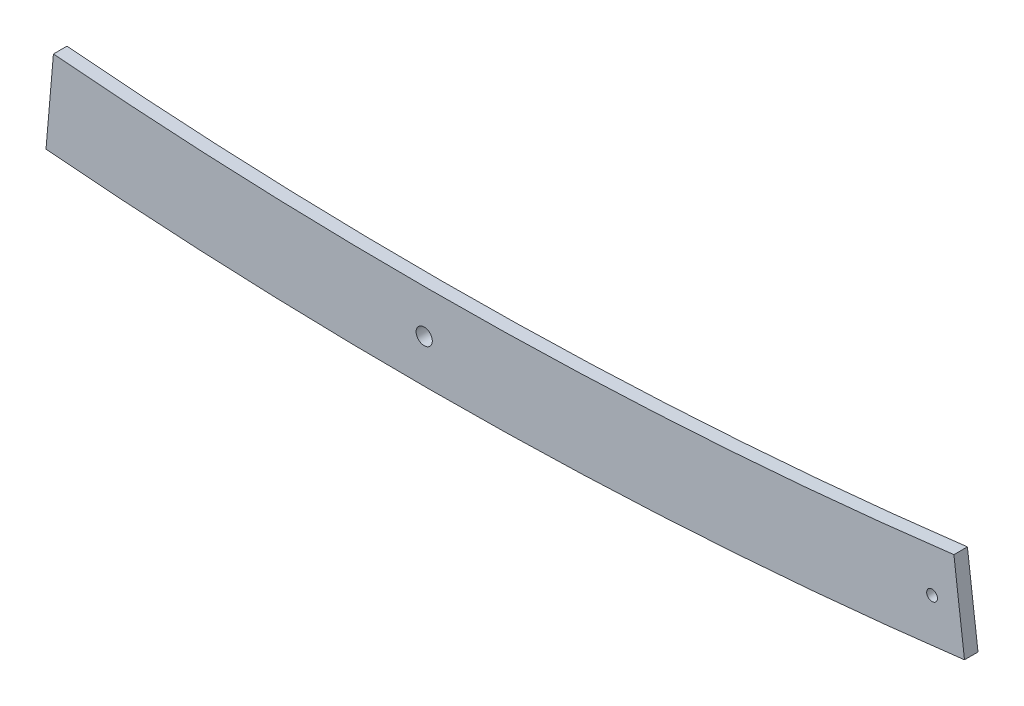
SolidWorks part; units mm, degrees
ref_plane "Front Plane" through (0, 0, 0) normal (0, 0, 1) x (1, 0, 0)
ref_plane "Top Plane" through (0, 0, 0) normal (0, 1, 0) x (1, 0, 0)
ref_plane "Right Plane" through (0, 0, 0) normal (1, 0, 0) x (0, 0, -1)
sketch "Sketch1" plane through (0, 0, 0) normal (0, 0, 1) x (1, 0, 0)
  line L0 (100, 6.1506) -> (98.0392, 22.03)
  line L1 (-70, 3.008) -> (-68.6275, 18.949)
  arc A0 (-70, 3.008) -> (100, 6.1506) centre (0, 816) ccw
  arc A1 (-68.6275, 18.949) -> (98.0392, 22.03) centre (0, 816) ccw
extrude "Boss-Extrude1" add sketch "Sketch1" along normal mid plane 2.5
sketch "Sketch2" plane through (0, 0, 0) normal (0, 0, 1) x (1, 0, 0)
  circle A0 centre (0, 8) radius 1.5
  dimension "D1" = 3
extrude "Cut-Extrude1" cut sketch "Sketch2" against normal mid plane 20
sketch "Sketch3" plane through (0, 0, 0) normal (0, 0, 1) x (1, 0, 0)
  circle A0 centre (94, 13.487) radius 1
  dimension "D1" = 2
extrude "Cut-Extrude2" cut sketch "Sketch3" against normal mid plane 20
